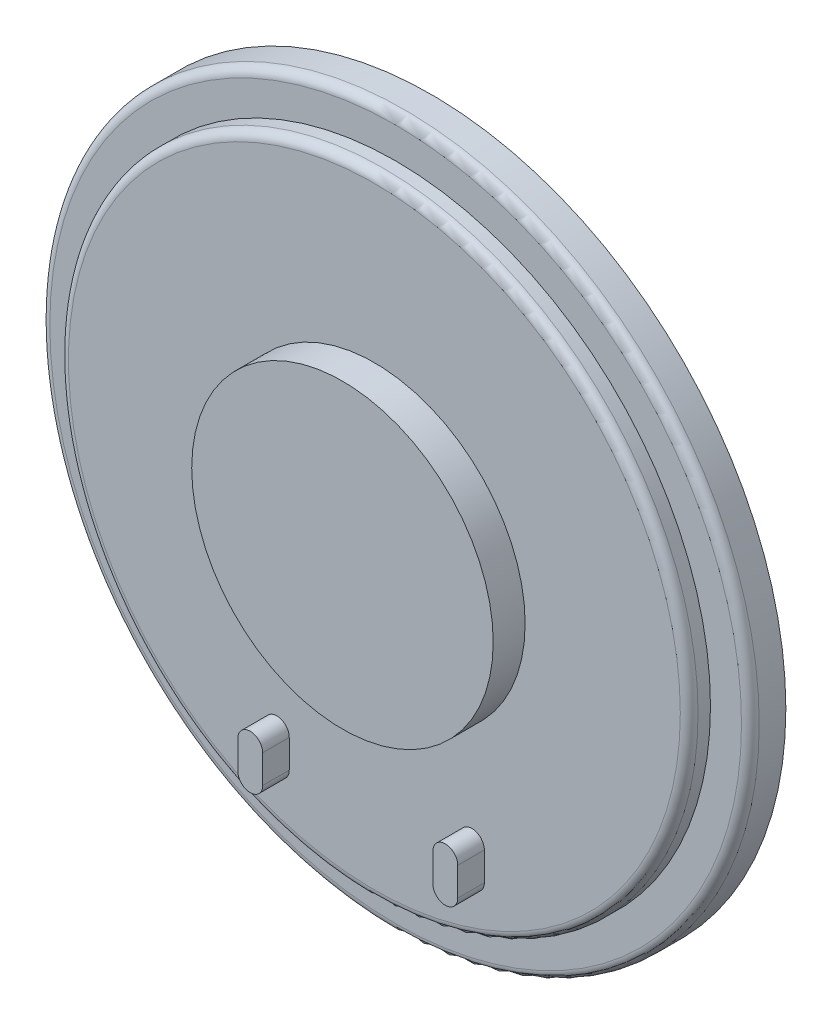
SolidWorks part; units mm, degrees
ref_plane "前视基准面" through (0, 0, 0) normal (0, 0, 1) x (1, 0, 0)
ref_plane "上视基准面" through (0, 0, 0) normal (0, 1, 0) x (1, 0, 0)
ref_plane "右视基准面" through (0, 0, 0) normal (1, 0, 0) x (0, 0, -1)
sketch "草图1" plane through (0, 0, 0) normal (0, 0, 1) x (1, 0, 0)
  circle A0 centre (0, 0) radius 20
  dimension "D1" = 40
extrude "拉伸1" add sketch "草图1" along normal blind 5
sketch "草图2" plane through (0, 0, 5) normal (0, 0, 1) x (1, 0, 0)
  circle A0 centre (0, 0) radius 17.75
  dimension "D1" = 35.5
extrude "切除-拉伸1" cut sketch "草图2" against normal offset from surface (3 mm away) 2 flip side to cut up to face at (20, 0, 0)
sketch "草图3" plane through (0, 0, 5) normal (0, 0, 1) x (1, 0, 0)
  circle A0 centre (0, 0) radius 8.5
  dimension "D1" = 17
extrude "切除-拉伸2" cut sketch "草图3" against normal blind 1.8 flip side to cut
sketch "草图4" plane through (0, 0, 0) normal (0, 0, -1) x (-1, 0, 0)
  circle A0 centre (0, 0) radius 17.75
  dimension "D1" = 35.5
extrude "切除-拉伸3" cut sketch "草图4" against normal blind 1.8
fillet "圆角1" radius 1.5 1 edges at (-17.75, 0, 0)
fillet "圆角2" radius 0.5 1 edges at (20, 0, 2)
fillet "圆角3" radius 0.5 1 edges at (17.75, 0, 3.2)
sketch "草图5" plane through (0, 0, 3.2) normal (0, 0, 1) x (1, 0, 0)
  line L0 (0, 24.0208) -> (0, -25.054) construction
  line L1 (-21.3641, -13) -> (22.8401, -13) construction
  line L2 (-5.5, -12.2) -> (-5.5, -13.8) construction
  line L3 (-4.8, -12.2) -> (-4.8, -13.8)
  line L4 (-6.2, -12.2) -> (-6.2, -13.8)
  line L5 (5.5, -12.2) -> (5.5, -13.8) construction
  line L6 (4.8, -12.2) -> (4.8, -13.8)
  line L7 (6.2, -12.2) -> (6.2, -13.8)
  arc A0 (-4.8, -12.2) -> (-6.2, -12.2) centre (-5.5, -12.2) ccw
  arc A1 (-6.2, -13.8) -> (-4.8, -13.8) centre (-5.5, -13.8) ccw
  arc A2 (4.8, -12.2) -> (6.2, -12.2) centre (5.5, -12.2) cw
  arc A3 (6.2, -13.8) -> (4.8, -13.8) centre (5.5, -13.8) cw
  point P7 (-5.5, -13)
  point P14 (5.5, -13)
  dimension "D1" = 13
  dimension "D2" = 1.4
  dimension "D3" = 1.6
  dimension "D4" = 11
extrude "接线焊盘" add sketch "草图5" along normal blind 1.5
